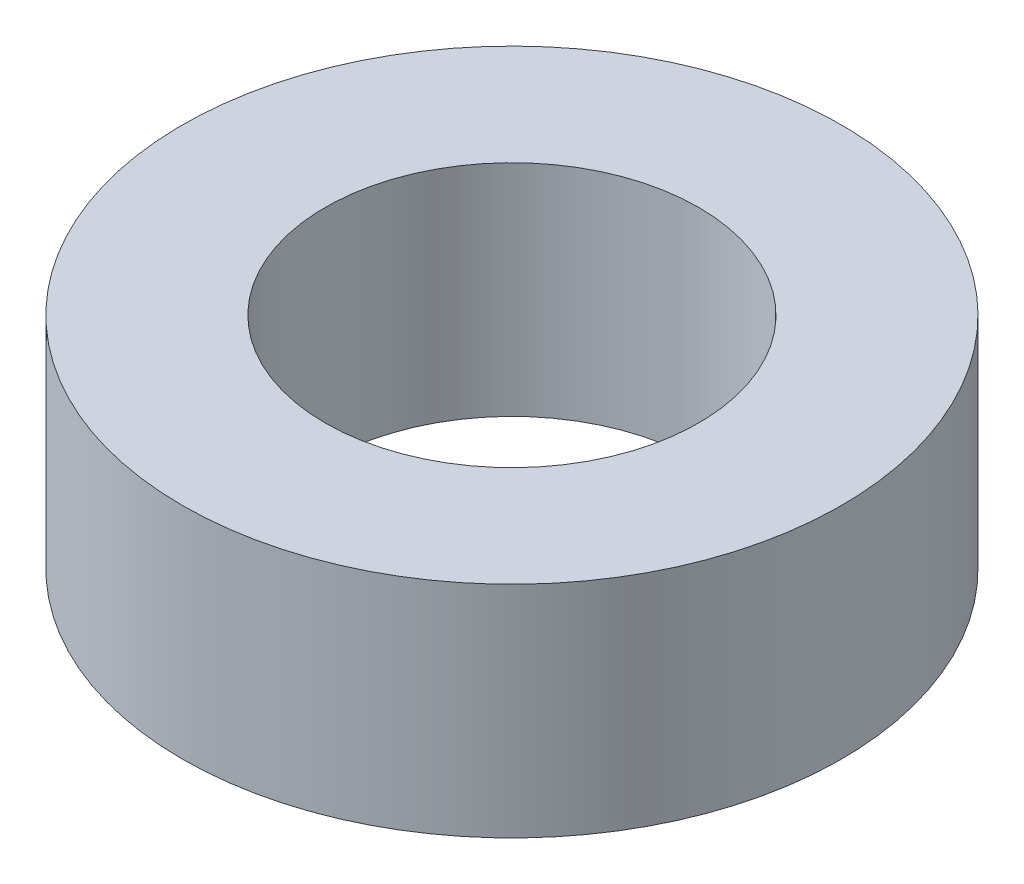
SolidWorks part; units mm, degrees
material "Д16Т ГОСТ 4784-97"
ref_plane "Front Plane" through (0, 0, 0) normal (0, 0, 1) x (1, 0, 0)
ref_plane "Top Plane" through (0, 0, 0) normal (0, 1, 0) x (1, 0, 0)
ref_plane "Right Plane" through (0, 0, 0) normal (1, 0, 0) x (0, 0, -1)
sketch "Sketch1" plane through (0, 0, 0) normal (0, 1, 0) x (1, 0, 0)
  circle A0 centre (0, 0) radius 15
  circle A1 centre (0, 0) radius 8.5
  dimension "D1" = 30
  dimension "D2" = 17
extrude "Boss-Extrude1" add sketch "Sketch1" along normal mid plane 10
